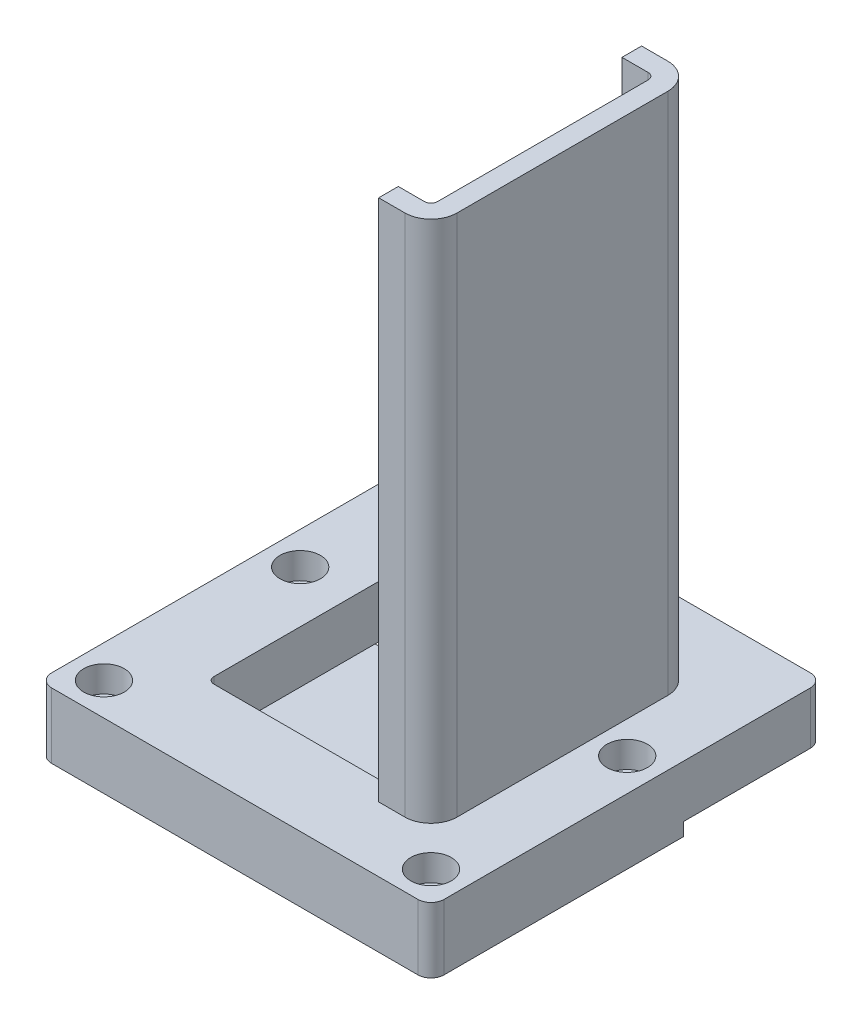
SolidWorks part; units mm, degrees
ref_plane "Front Plane" through (0, 0, 0) normal (0, 0, 1) x (1, 0, 0)
ref_plane "Top Plane" through (0, 0, 0) normal (0, 1, 0) x (1, 0, 0)
ref_plane "Right Plane" through (0, 0, 0) normal (1, 0, 0) x (0, 0, -1)
sketch "Sketch1" plane through (0, 0, 0) normal (0, 1, 0) x (1, 0, 0)
  line L1 (-38.1, -38.1) -> (38.1, -38.1)
  line L2 (-38.1, -38.1) -> (-38.1, 38.1)
  line L3 (-38.1, 38.1) -> (38.1, 38.1)
  line L4 (38.1, -38.1) -> (38.1, 38.1)
  line L5 (-38.1, -38.1) -> (38.1, 38.1) construction
  line L6 (-38.1, 38.1) -> (38.1, -38.1) construction
  point P0 (0, 0)
  dimension "D1" = 76.2
  dimension "D2" = 76.2
extrude "Boss-Extrude1" add sketch "Sketch1" along normal blind 12.7
sketch "Sketch2" plane through (0, 12.7, 0) normal (0, 1, 0) x (1, 0, 0)
  line L1 (-21.717, -21.717) -> (21.717, -21.717)
  line L2 (-21.717, -21.717) -> (-21.717, 21.717)
  line L3 (-21.717, 21.717) -> (21.717, 21.717)
  line L4 (21.717, -21.717) -> (21.717, 21.717)
  line L5 (-21.717, -21.717) -> (21.717, 21.717) construction
  line L6 (-21.717, 21.717) -> (21.717, -21.717) construction
  point P0 (0, 0)
  dimension "D1" = 43.434
  dimension "D2" = 43.434
extrude "Cut-Extrude1" cut sketch "Sketch2" against normal blind 10.16
fillet "Fillet1" radius 1.27 4 edges at (-21.717, 7.62, 21.717) (21.717, 7.62, 21.717) (21.717, 7.62, -21.717) (-21.717, 7.62, -21.717)
sketch "Sketch3" plane through (0, 2.54, 0) normal (0, 1, 0) x (1, 0, 0)
  line L0 (-21.717, 10.8585) -> (21.717, 10.8585)
  line L2 (-21.717, 10.8585) -> (-21.717, 20.447)
  line L3 (-20.447, 21.717) -> (20.447, 21.717)
  line L4 (21.717, 10.8585) -> (21.717, 20.447)
  line L5 (0, 0) -> (21.717, 21.717) construction
  line L6 (-21.717, 21.717) -> (0, 0) construction
  arc A0 (20.447, 21.717) -> (21.717, 20.447) centre (20.447, 20.447) cw
  arc A1 (-20.447, 21.717) -> (-21.717, 20.447) centre (-20.447, 20.447) ccw
  point P0 (0, 0)
  dimension "D2" = 1.27
  dimension "D1" = 10.8585
extrude "Cut-Extrude2" cut sketch "Sketch3" against normal through all
sketch "Sketch4" plane through (0, 12.7, 0) normal (0, 1, 0) x (1, 0, 0)
  line L1 (-31.75, -31.75) -> (31.75, -31.75) construction
  line L2 (-31.75, -31.75) -> (-31.75, 31.75) construction
  line L3 (-31.75, 31.75) -> (31.75, 31.75) construction
  line L4 (31.75, -31.75) -> (31.75, 31.75) construction
  line L5 (-31.75, -31.75) -> (31.75, 31.75) construction
  line L6 (-31.75, 31.75) -> (31.75, -31.75) construction
  circle A2 centre (31.75, -31.75) radius 2.54
  circle A3 centre (-31.75, -31.75) radius 2.54
  circle A4 centre (-31.75, 6.35) radius 2.54
  circle A5 centre (31.75, 6.35) radius 2.54
  point P0 (0, 0)
  dimension "D3" = 5.08
  dimension "D4" = 5.08
  dimension "D5" = 5.08
  dimension "D6" = 5.08
  dimension "D1" = 63.5
  dimension "D2" = 63.5
  dimension "D7" = 38.1
  dimension "D8" = 38.1
extrude "Cut-Extrude3" cut sketch "Sketch4" against normal through all
fillet "Fillet2" radius 2.54 4 edges at (-38.1, 6.35, 38.1) (38.1, 6.35, 38.1) (38.1, 6.35, -38.1) (-38.1, 6.35, -38.1)
sketch "Sketch5" plane through (0, 0, 0) normal (0, -1, 0) x (1, 0, 0)
  line L0 (38.1, 35.56) -> (38.1, -35.56) construction
  line L1 (38.1, -10.922) -> (-38.1, -10.922)
  line L2 (38.1, -10.922) -> (38.1, -38.1)
  line L3 (38.1, -38.1) -> (-38.1, -38.1)
  line L4 (-38.1, -10.922) -> (-38.1, -38.1)
  line L5 (35.56, -38.1) -> (-35.56, -38.1) construction
  dimension "D1" = 27.178
  dimension "D2" = 0
extrude "Cut-Extrude4" cut sketch "Sketch5" against normal blind 2.54
sketch "Sketch6" plane through (0, 12.7, 0) normal (0, 1, 0) x (1, 0, 0)
  line L0 (21.717, 20.447) -> (21.717, -20.447)
  line L1 (20.447, 21.717) -> (15.367, 21.717)
  line L2 (20.447, 21.717) -> (-20.447, 21.717) construction
  line L3 (15.367, 21.717) -> (15.367, 25.527)
  line L4 (15.367, 25.527) -> (20.447, 25.527)
  line L5 (25.527, 20.447) -> (25.527, -20.447)
  line L6 (0, 0) -> (11.484, 0) construction
  line L8 (15.367, -21.717) -> (15.367, -25.527)
  line L9 (20.447, -21.717) -> (15.367, -21.717)
  line L10 (15.367, -25.527) -> (20.447, -25.527)
  arc A0 (21.717, 20.447) -> (20.447, 21.717) centre (20.447, 20.447) ccw
  arc A1 (21.717, 20.447) -> (20.447, 21.717) centre (20.447, 20.447) ccw construction
  arc A2 (20.447, 25.527) -> (25.527, 20.447) centre (20.447, 20.447) cw
  arc A3 (20.447, -25.527) -> (25.527, -20.447) centre (20.447, -20.447) ccw
  arc A4 (21.717, -20.447) -> (20.447, -21.717) centre (20.447, -20.447) cw
  dimension "D1" = 3.81
  dimension "D2" = 3.81
  dimension "D3" = 6.35
extrude "Boss-Extrude2" add sketch "Sketch6" along normal blind 101.6
sketch "Sketch8" plane through (-38.1, 0, 0) normal (-1, 0, 0) x (0, 0, 1)
  line L0 (-8.0427, 4.3733) -> (34.0862, 4.3733) construction
  text T0 "<b>BUTTER</b>" font "Century Gothic" height in points 20
  point P2 (34.0862, 4.3733)
extrude "Cut-Extrude6" cut sketch "Sketch8" against normal blind 1.27
sketch "Sketch9" plane through (0, 12.7, 0) normal (0, 1, 0) x (1, 0, 0)
  circle A0 centre (-31.75, 6.35) radius 3.937
  circle A1 centre (-31.75, -31.75) radius 3.937
  circle A2 centre (31.75, -31.75) radius 3.937
  circle A3 centre (31.75, 6.35) radius 3.937
  dimension "D1" = 7.874
  dimension "D2" = 7.874
  dimension "D3" = 7.874
  dimension "D4" = 7.874
extrude "Cut-Extrude7" cut sketch "Sketch9" against normal blind 5.08
